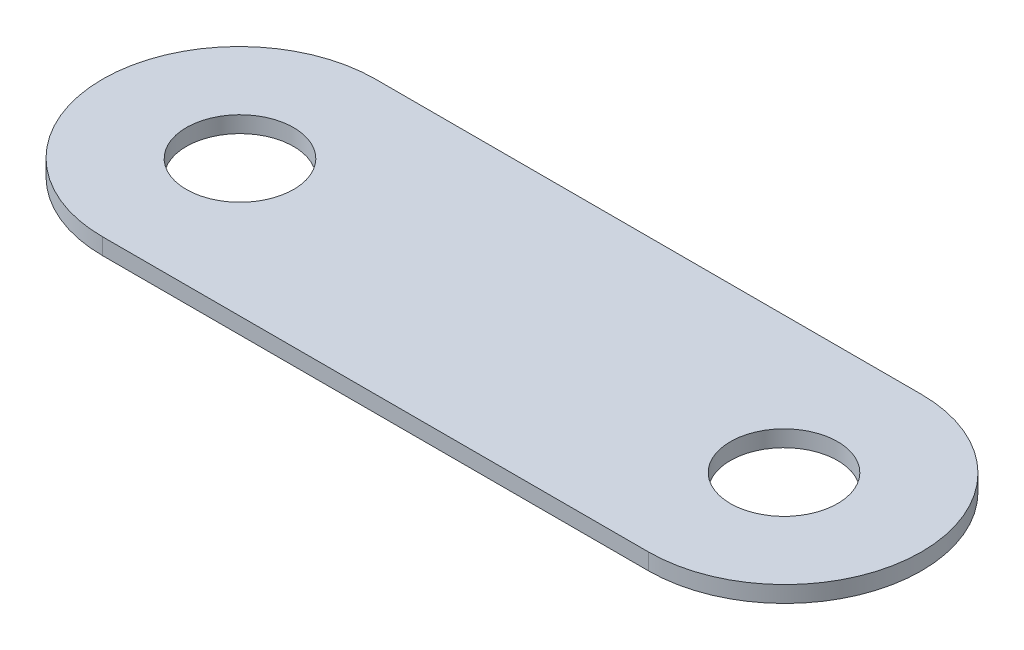
SolidWorks part; units mm, degrees
material "AISI 316 Stainless Steel Sheet (SS)"
ref_plane "Front Plane" through (0, 0, 0) normal (0, 0, 1) x (1, 0, 0)
ref_plane "Top Plane" through (0, 0, 0) normal (0, 1, 0) x (1, 0, 0)
ref_plane "Right Plane" through (0, 0, 0) normal (1, 0, 0) x (0, 0, -1)
sketch "Sketch1" plane through (0, 0, 0) normal (0, 1, 0) x (1, 0, 0)
  line L0 (-20, 0) -> (20, 0) construction
  line L1 (-20, 10) -> (20, 10)
  line L2 (-20, -10) -> (20, -10)
  arc A0 (-20, 10) -> (-20, -10) centre (-20, 0) ccw
  arc A1 (20, -10) -> (20, 10) centre (20, 0) ccw
  point P2 (0, 0)
  dimension "D1" = 20
  dimension "D2" = 40
extrude "Boss-Extrude1" add sketch "Sketch1" along normal blind 1.2
sketch "Sketch2" plane through (0, 1.2, 0) normal (0, 1, 0) x (1, 0, 0)
  line L0 (-19.93, 0) -> (19.93, 0) construction
  circle A0 centre (-19.93, 0) radius 3.93
  circle A1 centre (19.93, 0) radius 3.93
  point P5 (-16, 0)
  point P6 (16, 0)
  dimension "D2" = 7.86
  dimension "D1" = 32
extrude "Cut-Extrude1" cut sketch "Sketch2" against normal through all
